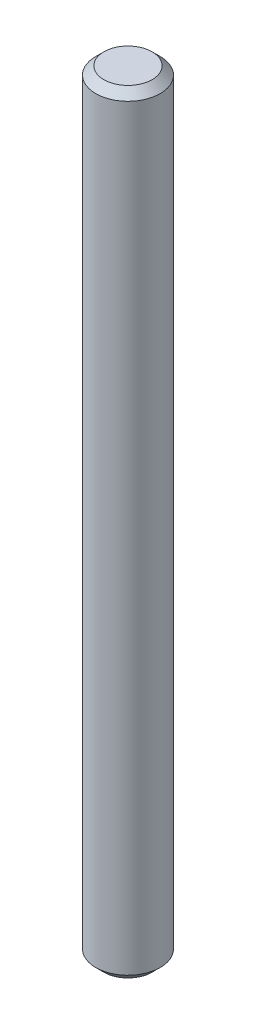
SolidWorks part; units mm, degrees
ref_plane "Front Plane" through (0, 0, 0) normal (0, 0, 1) x (1, 0, 0)
ref_plane "Top Plane" through (0, 0, 0) normal (0, 1, 0) x (1, 0, 0)
ref_plane "Right Plane" through (0, 0, 0) normal (1, 0, 0) x (0, 0, -1)
sketch "Sketch1" plane through (0, 0, 0) normal (0, 1, 0) x (1, 0, 0)
  circle A0 centre (0, 0) radius 2
  dimension "D1" = 4
extrude "Extrude1" add sketch "Sketch1" along normal mid plane 48
chamfer "Chamfer1" distance 0.5 angle 45 2 edges at (0, -24, 2) (0, 24, 2)
